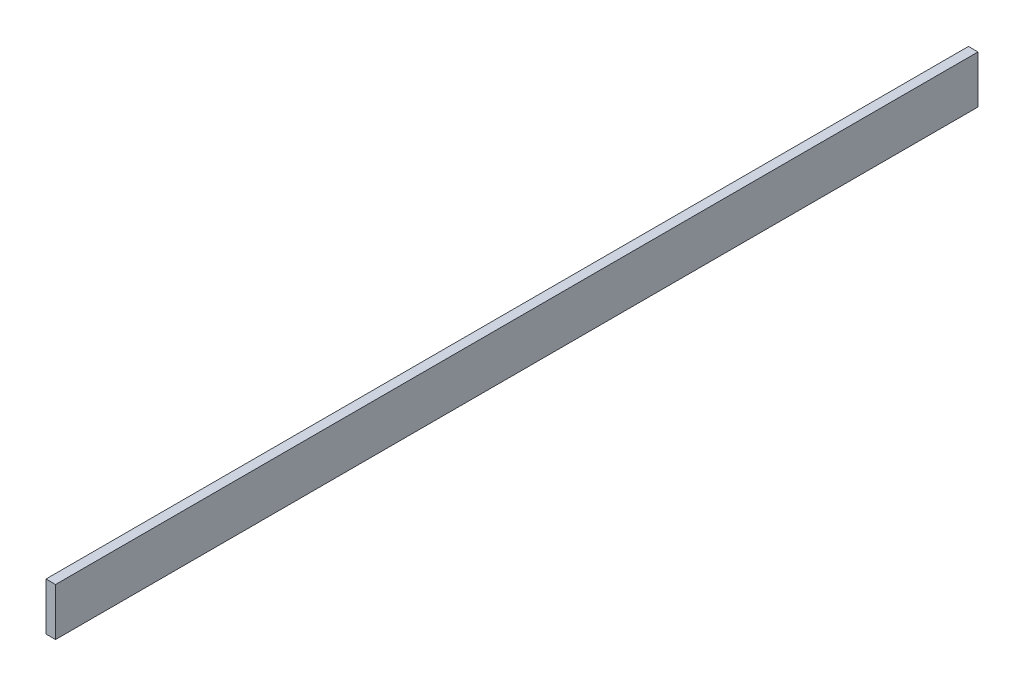
SolidWorks part; units mm, degrees
ref_plane "Ön Düzlem" through (0, 0, 0) normal (0, 0, 1) x (1, 0, 0)
ref_plane "Üst Düzlem" through (0, 0, 0) normal (0, 1, 0) x (1, 0, 0)
ref_plane "Sağ Düzlem" through (0, 0, 0) normal (1, 0, 0) x (0, 0, -1)
sketch "Çizim1" plane through (0, 0, 0) normal (1, 0, 0) x (0, 0, -1)
  line L1 (0, 0) -> (290, 0)
  line L2 (0, 0) -> (0, 15)
  line L3 (0, 15) -> (290, 15)
  line L4 (290, 0) -> (290, 15)
  dimension "D1" = 15
  dimension "D2" = 290
extrude "Yükseklik-Ekstrüzyon1" add sketch "Çizim1" along normal blind 3
